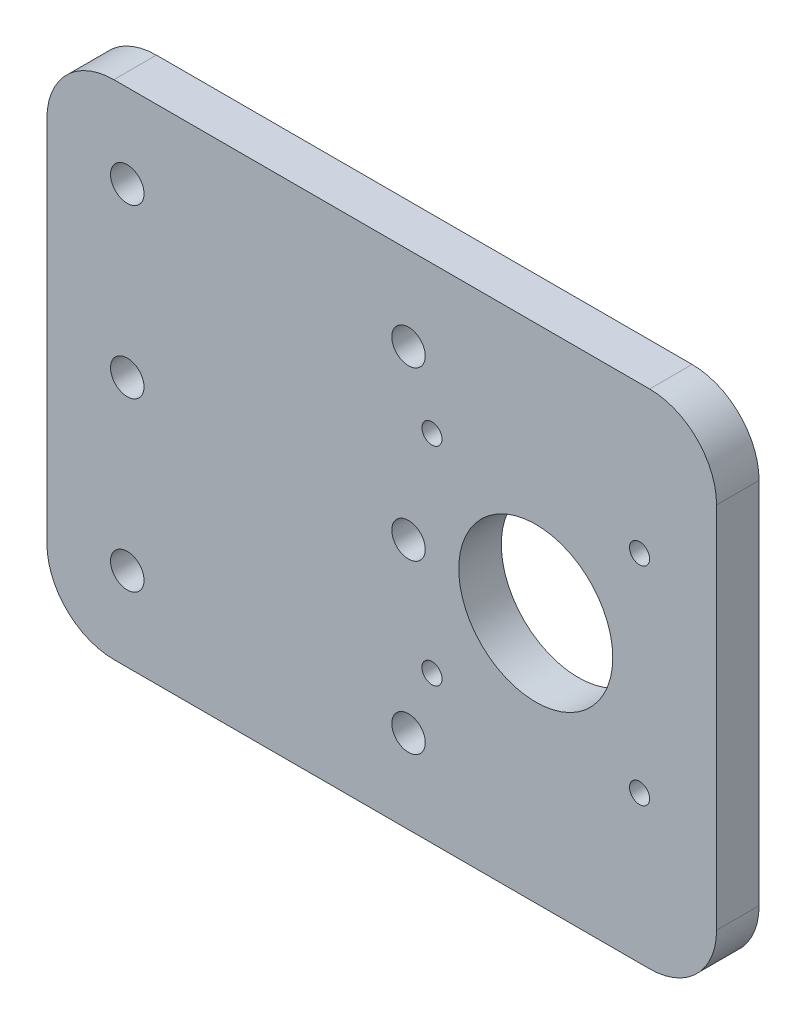
SolidWorks part; units mm, degrees
ref_plane "Front Plane" through (0, 0, 0) normal (0, 0, 1) x (1, 0, 0)
ref_plane "Top Plane" through (0, 0, 0) normal (0, 1, 0) x (1, 0, 0)
ref_plane "Right Plane" through (0, 0, 0) normal (1, 0, 0) x (0, 0, -1)
sketch "Sketch1" plane through (0, 0, 0) normal (0, 0, 1) x (1, 0, 0)
  line L1 (0, 0) -> (100, 0)
  line L2 (0, 0) -> (0, 75)
  line L3 (0, 75) -> (100, 75)
  line L4 (100, 0) -> (100, 75)
  dimension "D1" = 75
  dimension "D2" = 100
extrude "plate" add sketch "Sketch1" along normal blind 6.35
sketch "Sketch2" plane through (0, 0, 6.35) normal (0, 0, 1) x (1, 0, 0)
  line L0 (12, 75) -> (12, 0) construction
  line L1 (100, 75) -> (0, 75) construction
  line L2 (0, 0) -> (100, 0) construction
  line L3 (54, 75) -> (54, 0) construction
  line L4 (17, 75) -> (17, 0) construction
  line L5 (49, 75) -> (49, 0) construction
  line L6 (0, 75) -> (0, 0) construction
  line L7 (33, 75) -> (33, 0) construction
  line L8 (17, 0) -> (49, 75) construction
  circle A0 centre (12, 62.5) radius 2.5
  circle A1 centre (12, 12.5) radius 2.5
  circle A2 centre (54, 37.5) radius 2.5
  circle A3 centre (54, 62.5) radius 2.5
  circle A4 centre (12, 37.5) radius 2.5
  circle A5 centre (54, 12.5) radius 2.5
  point P20 (12, 37.5)
  point P23 (33, 37.5)
  dimension "D5" = 5
  dimension "D1" = 5
  dimension "D2" = 5
  dimension "D3" = 32
  dimension "D4" = 12
  dimension "D6" = 50
  dimension "D7" = 25
extrude "cut idler holes" cut sketch "Sketch2" against normal through all
sketch "Sketch3" plane through (0, 0, 6.35) normal (0, 0, 1) x (1, 0, 0)
  line L0 (0, 37.5) -> (100, 37.5) construction
  line L1 (57.5, 22) -> (88.5, 22) construction
  line L2 (57.5, 22) -> (57.5, 53) construction
  line L3 (57.5, 53) -> (88.5, 53) construction
  line L4 (88.5, 22) -> (88.5, 53) construction
  line L5 (57.5, 22) -> (88.5, 53) construction
  line L6 (57.5, 53) -> (88.5, 22) construction
  line L7 (0, 75) -> (0, 0) construction
  line L8 (100, 0) -> (100, 75) construction
  line L9 (33, 75) -> (33, 0) construction
  circle A0 centre (57.5, 53) radius 1.5
  circle A1 centre (88.5, 53) radius 1.5
  circle A2 centre (88.5, 22) radius 1.5
  circle A3 centre (57.5, 22) radius 1.5
  circle A4 centre (73, 37.5) radius 11.5
  point P0 (73, 37.5)
  dimension "D1" = 3
  dimension "D2" = 23
  dimension "D3" = 31
  dimension "D4" = 40
extrude "cut motor holes" cut sketch "Sketch3" against normal through all
ref_plane "Plane1" through (33, 0, 0) normal (1, 0, 0) x (0, 0, -1)
chamfer "Chamfer1" distance 1.5 angle 45 4 edges at (90, 22, 0) (59, 22, 0) (90, 53, 0) (59, 53, 0)
fillet "Fillet1" radius 10 4 edges at (0, 75, 3.175) (100, 0, 3.175) (0, 0, 3.175) (100, 75, 3.175)
equation "\"D7@Sketch2\"=0.5*\"D6@Sketch2\""
